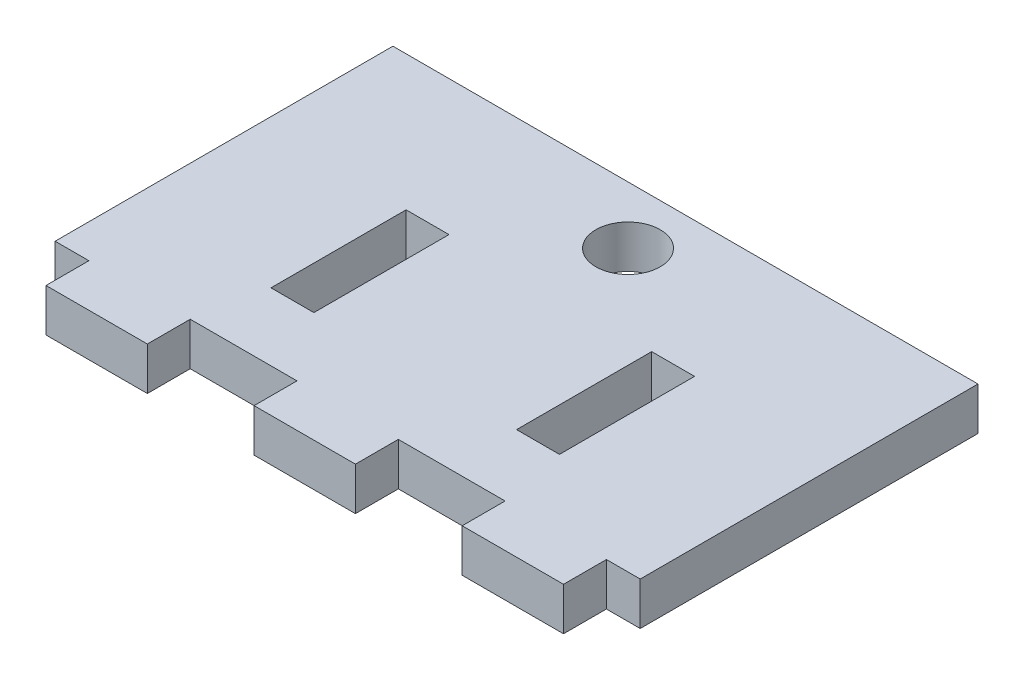
SolidWorks part; units mm, degrees
material "ABS"
ref_plane "Plan de face" through (0, 0, 0) normal (0, 0, 1) x (1, 0, 0)
ref_plane "Plan de dessus" through (0, 0, 0) normal (0, 1, 0) x (1, 0, 0)
ref_plane "Plan de droite" through (0, 0, 0) normal (1, 0, 0) x (0, 0, -1)
sketch "Esquisse2" plane through (0, 0, 0) normal (0, 1, 0) x (1, 0, 0)
  line L0 (-43.3013, 0) -> (43.3013, 0) construction
  line L1 (-43.3013, 25) -> (43.3013, 25)
  line L2 (-43.3013, 25) -> (-43.3013, -25)
  line L3 (-43.3013, -25) -> (43.3013, -25)
  line L4 (43.3013, 25) -> (43.3013, -25)
  line L5 (0, 100) -> (-43.3013, 25) construction
  line L6 (0, 100) -> (43.3013, 25) construction
  line L7 (0, 100) -> (0, 0) construction
  circle A0 centre (0, 100) radius 75 construction
  point P8 (0, 0)
  dimension "D2" = 150
  dimension "D1" = 50
  dimension "D3" = 60
extrude "Boss.-Extru.1" add sketch "Esquisse2" along normal blind 6.35
sketch "Sketch1" plane through (0, 6.35, 0) normal (0, 1, 0) x (1, 0, 0)
  circle A0 centre (0, 16.5) radius 4.7625
  circle A1 centre (0, 16.5) radius 7.1438 construction
  dimension "D1" = 9.525
  dimension "D2" = 0
extrude "Cut-Extrude1" cut sketch "Sketch1" against normal up to surface (6.35 mm away) up to face at (0, 0, 0)
sketch "Esquisse3" plane through (0, 0, 25) normal (0, 0, 1) x (1, 0, 0)
  line L0 (-43.3013, 6.35) -> (43.3013, 6.35) construction
  line L1 (38.3013, 0) -> (23.3013, 0)
  line L2 (38.3013, 0) -> (38.3013, 6.35)
  line L3 (38.3013, 6.35) -> (23.3013, 6.35)
  line L4 (23.3013, 0) -> (23.3013, 6.35)
  line L5 (-43.3013, 0) -> (43.3013, 0) construction
  line L6 (-38.3013, 0) -> (-23.3013, 0)
  line L7 (-38.3013, 0) -> (-38.3013, 6.35)
  line L8 (-38.3013, 6.35) -> (-23.3013, 6.35)
  line L9 (-23.3013, 0) -> (-23.3013, 6.35)
  line L10 (7.5, 0) -> (-7.5, 0)
  line L11 (7.5, 0) -> (7.5, 6.35)
  line L12 (7.5, 6.35) -> (-7.5, 6.35)
  line L13 (-7.5, 0) -> (-7.5, 6.35)
  line L14 (43.3013, 6.35) -> (43.3013, 0) construction
  line L15 (-43.3013, 6.35) -> (-43.3013, 0) construction
  point P18 (0, 0)
  point P20 (0, 0)
  point P23 (43.3013, 3.175)
  dimension "D1" = 15
  dimension "D2" = 15
  dimension "D3" = 15
  dimension "D4" = 5
  dimension "D5" = 5
extrude "Boss.-Extru.2" add sketch "Esquisse3" along normal blind 6.35
sketch "Esquisse4" plane through (0, 0, 0) normal (0, -1, 0) x (1, 0, 0)
  line L1 (21.35, -5) -> (15, -5)
  line L2 (21.35, -5) -> (21.35, 15)
  line L3 (21.35, 15) -> (15, 15)
  line L4 (15, -5) -> (15, 15)
  line L5 (-21.35, -5) -> (-15, -5)
  line L6 (-21.35, -5) -> (-21.35, 15)
  line L7 (-21.35, 15) -> (-15, 15)
  line L8 (-15, -5) -> (-15, 15)
extrude "Enlèv. mat.-Extru.1" cut sketch "Esquisse4" against normal blind 6.35
